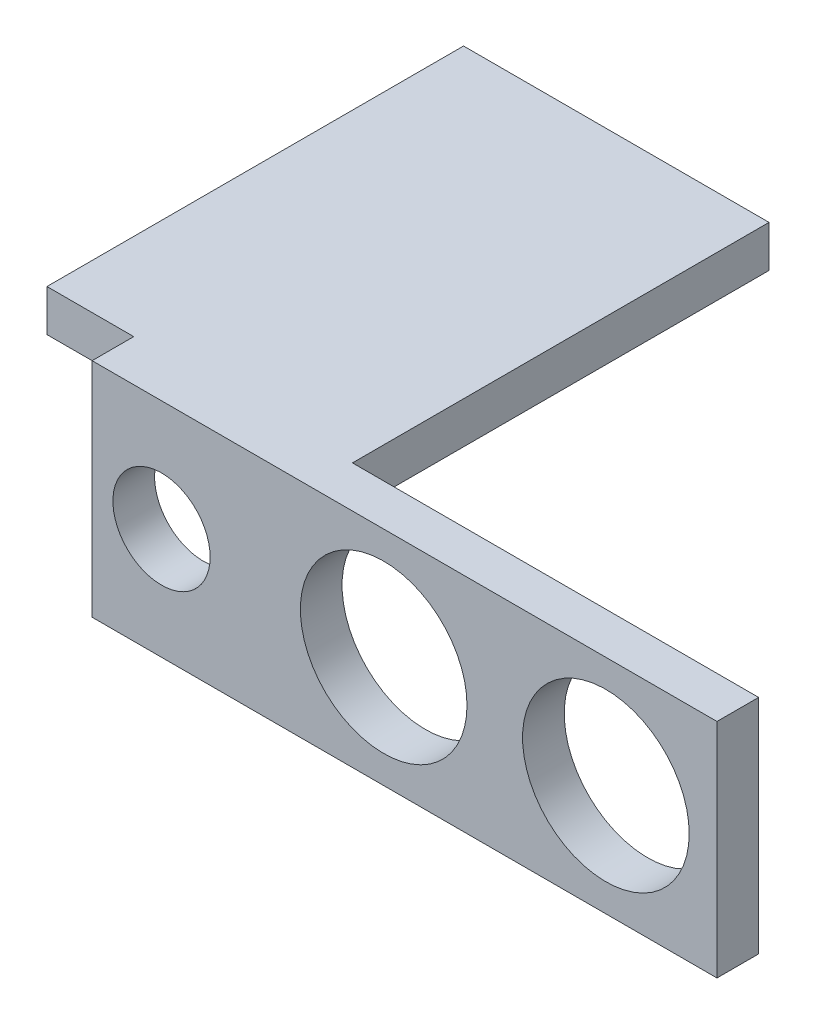
SolidWorks part; units mm, degrees
ref_plane "Front Plane" through (0, 0, 0) normal (0, 0, 1) x (1, 0, 0)
ref_plane "Top Plane" through (0, 0, 0) normal (0, 1, 0) x (1, 0, 0)
ref_plane "Right Plane" through (0, 0, 0) normal (1, 0, 0) x (0, 0, -1)
sketch "Sketch1" plane through (0, 0, 0) normal (0, 0, 1) x (1, 0, 0)
  line L1 (0, 0) -> (45, 0)
  line L2 (0, 0) -> (0, -16)
  line L3 (0, -16) -> (45, -16)
  line L4 (45, 0) -> (45, -16)
  circle A0 centre (5, -8) radius 3.5
  circle A1 centre (21, -8) radius 6
  circle A2 centre (37, -8) radius 6
  dimension "D1" = 16
  dimension "D2" = 12
  dimension "D3" = 7
  dimension "D5" = 8
  dimension "D6" = 5
  dimension "D8" = 12
  dimension "D9" = 16
  dimension "D4" = 16
  dimension "D7" = 45
extrude "Boss-Extrude1" add sketch "Sketch1" along normal blind 3
sketch "Sketch3" plane through (0, 0, 0) normal (0, 0, -1) x (-1, 0, 0)
  line L0 (-45, 0) -> (0, 0) construction
  line L5 (-15.75, 0) -> (6.25, 0)
  line L6 (-15.75, 0) -> (-15.75, -3)
  line L7 (-15.75, -3) -> (6.25, -3)
  line L8 (6.25, 0) -> (6.25, -3)
  line L9 (0, 0) -> (0, -16) construction
  dimension "D1" = 3
  dimension "D2" = 22
  dimension "D3" = 6.25
extrude "Boss-Extrude3" add sketch "Sketch3" along normal blind 30
sketch "Sketch4" plane through (0, -3, 0) normal (0, -1, 0) x (1, 0, 0)
  circle A0 centre (12.306, -22.8462) radius 1.0922
  circle A1 centre (-2.5402, -22.8462) radius 1.0922
  dimension "D1" = 2.1844
  dimension "D2" = 2.1844
